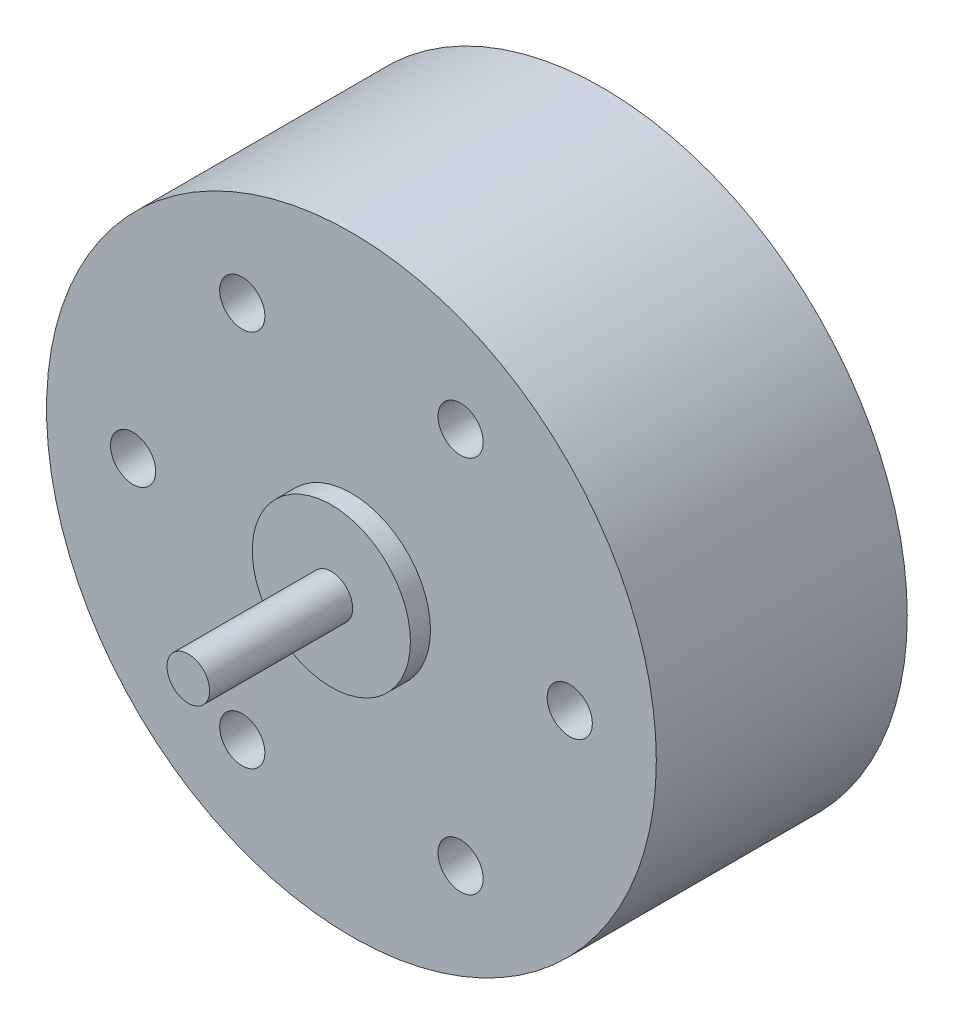
SolidWorks part; units mm, degrees
ref_plane "Front Plane" through (0, 0, 0) normal (0, 0, 1) x (1, 0, 0)
ref_plane "Top Plane" through (0, 0, 0) normal (0, 1, 0) x (1, 0, 0)
ref_plane "Right Plane" through (0, 0, 0) normal (1, 0, 0) x (0, 0, -1)
sketch "Sketch1" plane through (0, 0, 0) normal (0, 0, 1) x (1, 0, 0)
  circle A0 centre (0, 0) radius 12.15
  dimension "D1" = 24.3
extrude "Boss-Extrude1" add sketch "Sketch1" along normal blind 10
sketch "Sketch2" plane through (0, 0, 10) normal (0, 0, 1) x (1, 0, 0)
  circle A0 centre (0, 0) radius 3.15
  dimension "D1" = 6.3
extrude "Boss-Extrude2" add sketch "Sketch2" along normal blind 0.8
sketch "Sketch3" plane through (0, 0, 10.8) normal (0, 0, 1) x (1, 0, 0)
  circle A0 centre (0, 0) radius 0.85
  dimension "D1" = 1.7
extrude "Boss-Extrude3" add sketch "Sketch3" along normal blind 5.7
hole_wizard "M1.6 Clearance Hole1" positions "Sketch6" profile "Sketch5" hole size "M1.6" standard "ANSI Metric"
sketch "Sketch6" plane through (0, 0, 10) normal (0, 0, 1) x (1, 0, 0)
  line L0 (-12.15, 0) -> (12.15, 0) construction
  line L2 (-6.075, -10.5222) -> (6.075, 10.5222) construction
  line L4 (6.075, -10.5222) -> (-6.075, 10.5222) construction
  circle A0 centre (0, 0) radius 12.15 construction
  point P0 (-4.35, 7.5344)
  point P2 (4.35, 7.5344)
  point P4 (8.7, 0)
  point P6 (4.35, -7.5344)
  point P8 (-4.35, -7.5344)
  point P10 (-8.7, 0)
  dimension "D1" = 8.7
  dimension "D2" = 8.7
  dimension "D3" = 8.7
  dimension "D4" = 8.7
  dimension "D5" = 8.7
  dimension "D6" = 8.7
  dimension "D7" = 60
  dimension "D8" = 60
sketch "Sketch5" plane through (-4.35, 7.5344, 10) normal (1, 0, 0) x (0, -1, 0)
  line L0 (0, 0) -> (0, 3.5408)
  line L1 (0, 3.5408) -> (0.9, 3)
  line L2 (0.9, 3) -> (0.9, 0)
  line L5 (0.9, 0) -> (0, 0)
  line L10 (0, 3.5408) -> (-0.9, 3) construction
  line L11 (0, -6.35) -> (0, 107.95) construction
  dimension "Hole Dia." = 1.8
  dimension "Hole Depth" = 3
  dimension "Drill Angle" = 118
equation "\"D2@Sketch6\"=\"D1@Sketch6\""
equation "\"D4@Sketch6\"=\"D1@Sketch6\""
equation "\"D5@Sketch6\"=\"D1@Sketch6\""
equation "\"D6@Sketch6\"=\"D1@Sketch6\""
equation "\"D3@Sketch6\"=\"D1@Sketch6\""
